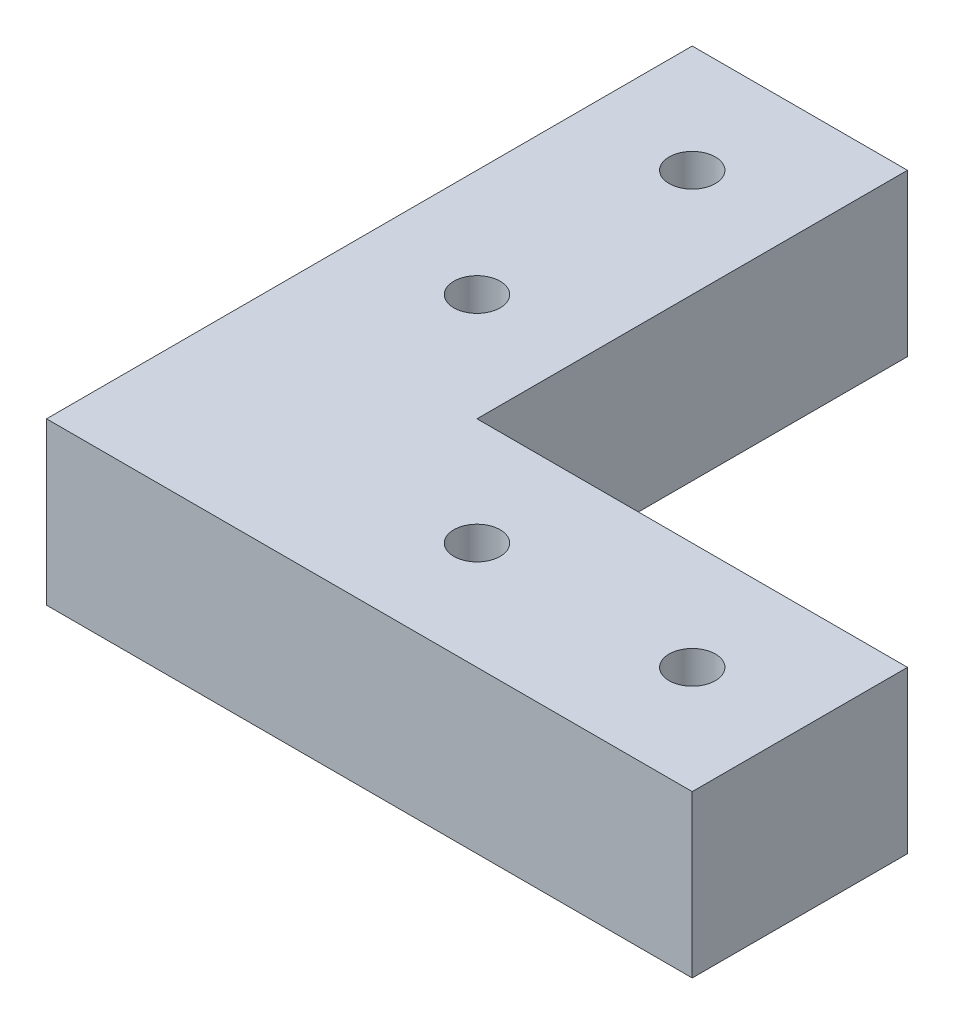
SolidWorks part; units mm, degrees
ref_plane "Front Plane" through (0, 0, 0) normal (0, 0, 1) x (1, 0, 0)
ref_plane "Top Plane" through (0, 0, 0) normal (0, 1, 0) x (1, 0, 0)
ref_plane "Right Plane" through (0, 0, 0) normal (1, 0, 0) x (0, 0, -1)
sketch "Sketch1" plane through (0, 0, 0) normal (0, 1, 0) x (1, 0, 0)
  line L0 (0, 0) -> (60, 0)
  line L1 (60, 0) -> (60, 20)
  line L2 (60, 20) -> (20, 20)
  line L3 (20, 20) -> (20, 60)
  line L4 (20, 60) -> (0, 60)
  line L5 (0, 60) -> (0, 0)
  circle A0 centre (50, 10) radius 2.15
  circle A1 centre (30, 10) radius 2.15
  circle A2 centre (10, 50) radius 2.15
  circle A3 centre (10, 30) radius 2.15
  dimension "D6" = 4.3
  dimension "D7" = 4.3
  dimension "D13" = 4.3
  dimension "D14" = 4.3
  dimension "D1" = 60
  dimension "D2" = 60
  dimension "D3" = 20
  dimension "D4" = 20
  dimension "D5" = 10
  dimension "D8" = 10
  dimension "D9" = 20
  dimension "D10" = 10
  dimension "D11" = 10
  dimension "D12" = 20
  dimension "D15" = 10
  dimension "D16" = 10
extrude "Boss-Extrude1" add sketch "Sketch1" along normal blind 15
